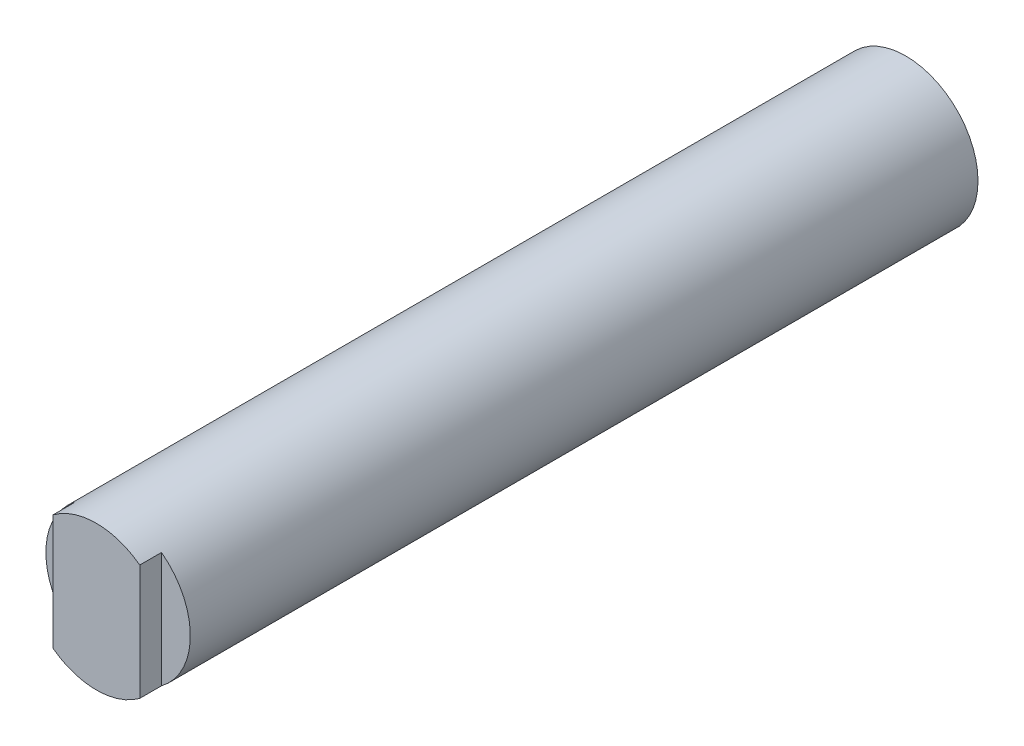
SolidWorks part; units mm, degrees
ref_plane "Front Plane" through (0, 0, 0) normal (0, 0, 1) x (1, 0, 0)
ref_plane "Top Plane" through (0, 0, 0) normal (0, 1, 0) x (1, 0, 0)
ref_plane "Right Plane" through (0, 0, 0) normal (1, 0, 0) x (0, 0, -1)
sketch "Sketch1" plane through (0, 0, 0) normal (0, 0, 1) x (1, 0, 0)
  circle A0 centre (0, 0) radius 26.3525
  dimension "D1" = 52.705
extrude "Boss-Extrude1" add sketch "Sketch1" along normal blind 295.275
sketch "Sketch2" plane through (0, 0, 295.275) normal (0, 0, 1) x (1, 0, 0)
  line L0 (-15.8369, 21.0629) -> (-15.8369, -21.0629)
  line L1 (-15.8369, -21.0629) -> (15.8369, -21.0629) construction
  line L2 (15.8369, -21.0629) -> (15.8369, 21.0629)
  circle A0 centre (0, 0) radius 26.3525 construction
  circle A1 centre (0, 0) radius 26.3525
  arc A2 (-15.8369, 21.0629) -> (-15.8369, -21.0629) centre (0, 0) ccw
  arc A3 (15.8369, -21.0629) -> (15.8369, 21.0629) centre (0, 0) ccw
  dimension "D2" = 31.6738
  dimension "D1" = 0
extrude "Cut-Extrude1" cut sketch "Sketch2" against normal blind 7.9375
